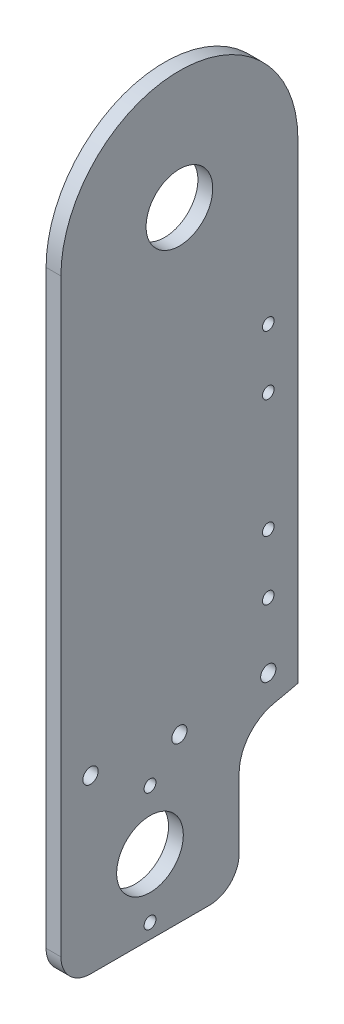
SolidWorks part; units mm, degrees
ref_plane "Front Plane" through (0, 0, 0) normal (1, 0, 0) x (0, 1, 0)
ref_plane "Top Plane" through (0, 0, 0) normal (0, 0, 1) x (0, 1, 0)
ref_plane "Right Plane" through (0, 0, 0) normal (0, 1, 0) x (-1, 0, 0)
sketch "Sketch1" plane through (0, 0, 0) normal (1, 0, 0) x (0, 1, 0)
  line L0 (0, -50.8) -> (-201.9899, -50.8)
  line L1 (0, 0) -> (-208.28, 0) construction
  line L2 (0, 0) -> (0, 50.8) construction
  line L3 (0, 0) -> (-208.28, 0) construction
  line L4 (0, 50.8) -> (-201.9899, 50.8)
  line L6 (-265.4899, 50.8) -> (-265.4899, 44.353) construction
  line L7 (-265.4899, -25.594) -> (-265.4899, -19.147) construction
  line L9 (-265.4899, 50.8) -> (-265.4899, -25.594)
  line L10 (-201.9899, 50.8) -> (-265.4899, 50.8)
  line L14 (-265.4899, -25.594) -> (-206.7015, -25.594)
  line L16 (-265.4899, -19.147) -> (-201.9899, -19.147) construction
  line L17 (-265.4899, -19.147) -> (-265.4899, 44.353) construction
  line L18 (-265.4899, 44.353) -> (-201.9899, 44.353) construction
  line L19 (-201.9899, -19.147) -> (-201.9899, 44.353) construction
  line L20 (-265.4899, -19.147) -> (-201.9899, 44.353) construction
  line L21 (-265.4899, 44.353) -> (-201.9899, -19.147) construction
  circle A0 centre (0, 0) radius 50.8 construction
  arc A1 (-201.9899, 50.8) -> (-201.9899, -50.8) centre (0, 0) ccw construction
  arc A2 (0, 50.8) -> (0, -50.8) centre (0, 0) cw
  arc A3 (-175.6828, 50.8) -> (-175.6828, -50.8) centre (0, 0) ccw construction
  arc A4 (-178.9855, 50.8) -> (-178.9855, -50.8) centre (0, 0) ccw construction
  arc A5 (-182.2837, 50.8) -> (-182.2837, -50.8) centre (0, 0) ccw construction
  circle A6 centre (0, 0) radius 14.2875
  arc A7 (-188.8674, 50.8) -> (-188.8674, -50.8) centre (0, 0) ccw construction
  arc A8 (-208.28, 0) -> (-201.9899, -50.8) centre (0, 0) ccw construction
  circle A9 centre (-233.7399, 12.603) radius 14.2875
  circle A10 centre (-233.7399, 12.603) radius 25.4 construction
  arc A11 (-188.8674, 50.8) -> (-191.8331, 38.1) centre (0, 0) ccw construction
  arc A12 (-191.8331, 38.1) -> (-195.58, 0) centre (0, 0) ccw construction
  arc A13 (-195.58, 0) -> (-191.8331, -38.1) centre (0, 0) ccw construction
  arc A14 (-191.8331, -38.1) -> (-188.8674, -50.8) centre (0, 0) ccw construction
  arc A15 (-206.7015, -25.594) -> (-201.9899, -50.8) centre (0, 0) ccw
  point P15 (-191.8331, -38.1)
  point P21 (-195.58, 0)
  point P22 (-191.8331, 38.1)
  point P24 (0, 0)
  point P31 (-206.7015, -25.594)
  point P36 (-259.1399, 12.603)
  point P37 (-208.3399, 12.603)
  point P38 (-304.4452, -46.27)
  dimension "D1" = 101.6
  dimension "D2" = 0
  dimension "D3" = 132.08
  dimension "D4" = 3.175
  dimension "D5" = 3.175
  dimension "D6" = 19.05
  dimension "D7" = 28.575
  dimension "D8" = 6.35
  dimension "D9" = 3
  dimension "D11" = 28.575
  dimension "D12" = 12.7
  dimension "D14" = 50.8
  dimension "D10" = 63.5
  dimension "D13" = 63.5
  dimension "D15" = 63.5
extrude "Boss-Extrude1" add sketch "Sketch1" along normal blind 6.35
sketch "Sketch4" plane through (6.35, 0, 0) normal (1, 0, 0) x (0, 1, 0)
  point P12 (0, 0)
  point P20 (-191.8331, -38.1)
  point P22 (-195.58, 0)
  point P24 (-191.8331, 38.1)
hole_wizard "F (0.257) Diameter Hole1" positions "Sketch4" profile "Sketch5" hole size "F" standard "ANSI Inch" end condition through all
sketch "Sketch5" plane through (6.35, 0, 0) normal (0, 1, 0) x (0, 0, -1)
  line L0 (0, 0) -> (0, 6.35)
  line L1 (0, 6.35) -> (3.2639, 6.35)
  line L2 (3.2639, 6.35) -> (3.2639, 0)
  line L5 (3.2639, 0) -> (0, 0)
  line L11 (0, -6.35) -> (0, 107.95) construction
  dimension "Thru Hole Dia." = 6.5278
  dimension "Thru Hole Depth" = 6.35
sketch "Sketch6" plane through (6.35, 0, 0) normal (1, 0, 0) x (0, 1, 0)
  point P0 (-259.1399, 12.603)
  point P2 (-208.3399, 12.603)
hole_wizard "#9 (0.2) Diameter Hole1" positions "Sketch6" profile "Sketch7" hole size "#9" standard "ANSI Inch" end condition through all
sketch "Sketch7" plane through (6.35, -259.1399, 12.603) normal (0, 1, 0) x (0, 0, -1)
  line L0 (0, 0) -> (0, 6.35)
  line L1 (0, 6.35) -> (2.54, 6.35)
  line L2 (2.54, 6.35) -> (2.54, 0)
  line L5 (2.54, 0) -> (0, 0)
  line L11 (0, -6.35) -> (0, 107.95) construction
  dimension "Thru Hole Dia." = 5.08
  dimension "Thru Hole Depth" = 6.35
fillet "Fillet2" radius 12.7 2 edges at (3.175, -265.4899, -25.594) (3.175, -265.4899, 50.8)
fillet "Fillet1" radius 19.05 1 edges at (3.175, -206.7015, -25.594)
sketch "Sketch8" plane through (6.35, 0, 0) normal (1, 0, 0) x (0, 1, 0)
  line L0 (-201.9899, -50.8) -> (0, -50.8) construction
  point P0 (-163.8899, -38.1)
  point P1 (-138.4899, -38.1)
  point P2 (-87.6899, -38.1)
  point P3 (-62.2899, -38.1)
  point P7 (0, 0)
  point P8 (0, 0)
  point P9 (0, 0)
  point P11 (0, 0)
  dimension "D1" = 25.4
  dimension "D2" = 25.4
  dimension "D3" = 12.7
  dimension "D4" = 50.8
  dimension "D5" = 38.1
hole_wizard "#9 (0.196) Diameter Hole1" positions "Sketch8" profile "Sketch9" hole size "#9" standard "ANSI Inch" end condition through all
sketch "Sketch9" plane through (6.35, -163.8899, -38.1) normal (0, 1, 0) x (0, 0, -1)
  line L0 (0, 0) -> (0, 6.35)
  line L1 (0, 6.35) -> (4.7625, 6.35)
  line L2 (2.4892, 4.0767) -> (2.4892, 0)
  line L5 (2.4892, 0) -> (0, 0)
  line L7 (4.7625, 6.35) -> (2.4892, 4.0767)
  line L8 (-4.7625, 6.35) -> (-2.4892, 4.0767) construction
  line L11 (0, -6.35) -> (0, 107.95) construction
  dimension "Thru Hole Dia." = 4.9784
  dimension "Thru Hole Depth" = 6.35
  dimension "Far C'Sink Dia." = 9.525
  dimension "Far C'Sink Angle" = 90
